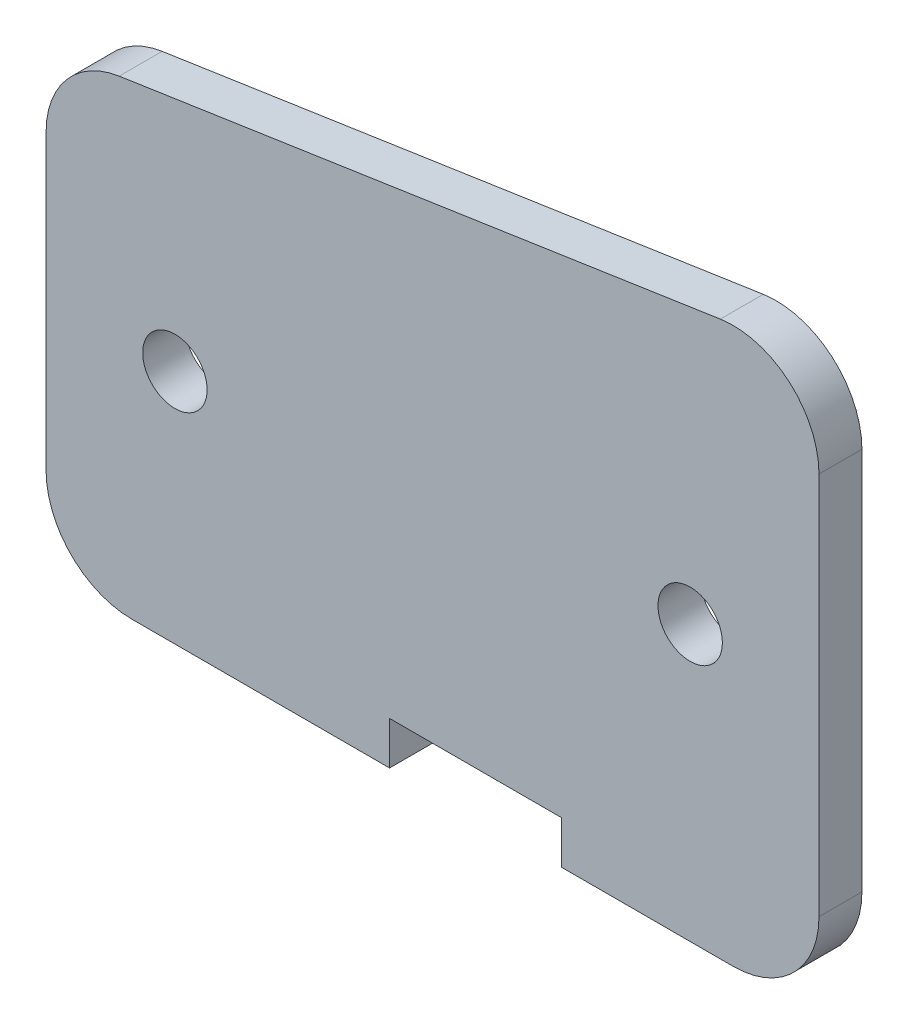
SolidWorks part; units mm, degrees
ref_plane "Front Plane" through (0, 0, 0) normal (0, 0, 1) x (1, 0, 0)
ref_plane "Top Plane" through (0, 0, 0) normal (0, 1, 0) x (1, 0, 0)
ref_plane "Right Plane" through (0, 0, 0) normal (1, 0, 0) x (0, 0, -1)
sketch "Sketch1" plane through (0, 0, 0) normal (0, 0, 1) x (1, 0, 0)
  line L0 (-174.625, 0) -> (-193.675, 0)
  line L7 (-152.4, 0) -> (-152.4, 40.64)
  line L8 (-190.5, 0) -> (-190.5, 34.925)
  line L13 (-142.875, 34.6952) -> (-142.875, 6.35)
  line L14 (-200.025, 28.0277) -> (-200.025, 6.35)
  line L15 (-194.617, 34.3075) -> (-150.167, 40.975)
  line L17 (-174.625, 0) -> (-174.625, 3.175)
  line L18 (-174.625, 3.175) -> (-161.925, 3.175)
  line L19 (-161.925, 0) -> (-161.925, 3.175)
  line L22 (-149.225, 0) -> (-161.925, 0)
  circle A0 centre (-190.5, 17.4625) radius 2.3813
  circle A1 centre (-152.4, 20.32) radius 2.3813
  arc A2 (-200.025, 6.35) -> (-193.675, 0) centre (-193.675, 6.35) ccw
  arc A3 (-142.875, 6.35) -> (-149.225, 0) centre (-149.225, 6.35) cw
  arc A4 (-142.875, 34.6952) -> (-150.167, 40.975) centre (-149.225, 34.6952) ccw
  arc A5 (-200.025, 28.0277) -> (-194.617, 34.3075) centre (-193.675, 28.0277) cw
  dimension "D9" = 4.7625
  dimension "D10" = 4.7625
  dimension "D2" = 6.35
  dimension "D7" = 9.525
  dimension "D8" = 9.525
  dimension "D11" = 3.175
  dimension "D12" = 12.7
  dimension "D13" = 9.525
extrude "Boss-Extrude1" add sketch "Sketch1" along normal blind 3.175 contours L7 A1 | L7 A1 | L15 A4 L13 A3 L22 L19 L18 L17 L0 A2 L14 A5 | A0
